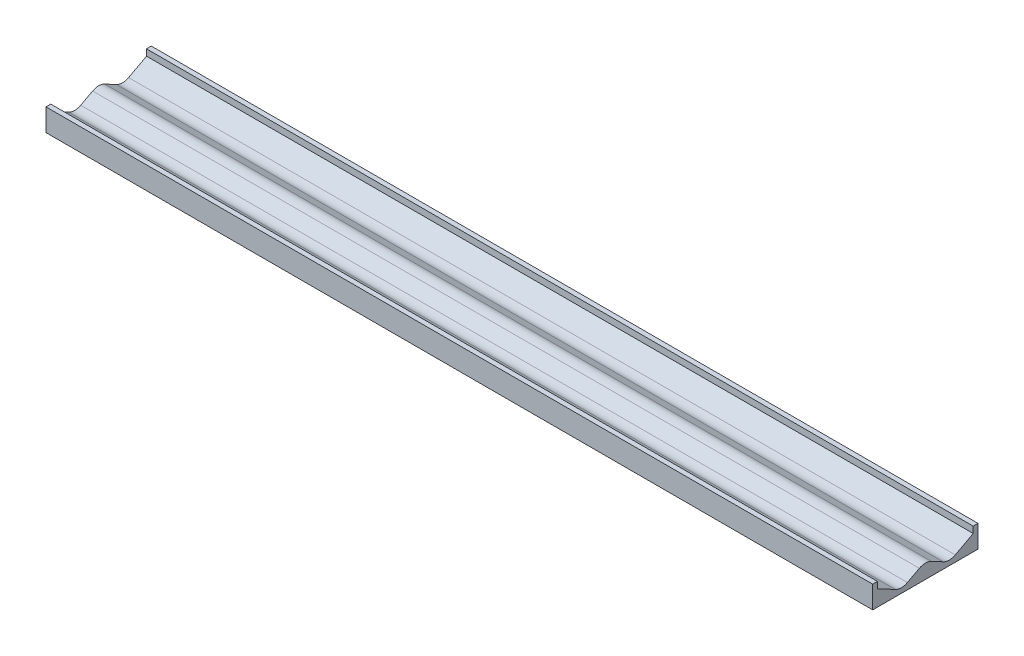
SolidWorks part; units mm, degrees
ref_plane "Ön Düzlem" through (0, 0, 0) normal (0, 0, 1) x (1, 0, 0)
ref_plane "Üst Düzlem" through (0, 0, 0) normal (0, 1, 0) x (1, 0, 0)
ref_plane "Sağ Düzlem" through (0, 0, 0) normal (1, 0, 0) x (0, 0, -1)
sketch "Çizim1" plane through (0, 0, 0) normal (0, 1, 0) x (1, 0, 0)
  line L1 (-129.525, -16.5) -> (129.525, -16.5)
  line L2 (-129.525, -16.5) -> (-129.525, 16.5)
  line L3 (-129.525, 16.5) -> (129.525, 16.5)
  line L4 (129.525, -16.5) -> (129.525, 16.5)
  line L5 (-129.525, -16.5) -> (129.525, 16.5) construction
  line L6 (-129.525, 16.5) -> (129.525, -16.5) construction
  point P0 (0, 0)
  dimension "D1" = 33
extrude "Yükseklik-Ekstrüzyon1" add sketch "Çizim1" along normal blind 7
sketch "Çizim2" plane through (129.525, 0, 0) normal (1, 0, 0) x (0, 0, -1)
  line L5 (-15, 7) -> (-15, 5)
  line L6 (-16.5, 7) -> (16.5, 7) construction
  line L7 (-15, 5) -> (15, 5)
  line L8 (15, 5) -> (15, 7)
  line L9 (15, 7) -> (-15, 7)
extrude "Kes-Ekstrüzyon1" cut sketch "Çizim2" against normal blind 291
sketch "Çizim3" plane through (129.525, 0, 0) normal (1, 0, 0) x (0, 0, -1)
  line L2 (-15, 5) -> (15, 5) construction
  line L3 (-15, 5) -> (15, 5)
  line L8 (-15, 5) -> (-9.3824, 2.0039)
  line L9 (-5.6176, 2.0039) -> (-1.8824, 3.9961)
  line L10 (1.8824, 3.9961) -> (5.6176, 2.0039)
  line L11 (9.3824, 2.0039) -> (15, 5)
  arc A0 (9.3824, 2.0039) -> (5.6176, 2.0039) centre (7.5, 5.5333) cw
  arc A1 (-5.6176, 2.0039) -> (-9.3824, 2.0039) centre (-7.5, 5.5333) cw
  arc A2 (1.8824, 3.9961) -> (-1.8824, 3.9961) centre (0, 0.4667) ccw
  point P16 (0, 5)
  dimension "D1" = 4
extrude "Kes-Ekstrüzyon2" cut sketch "Çizim3" against normal blind 291
